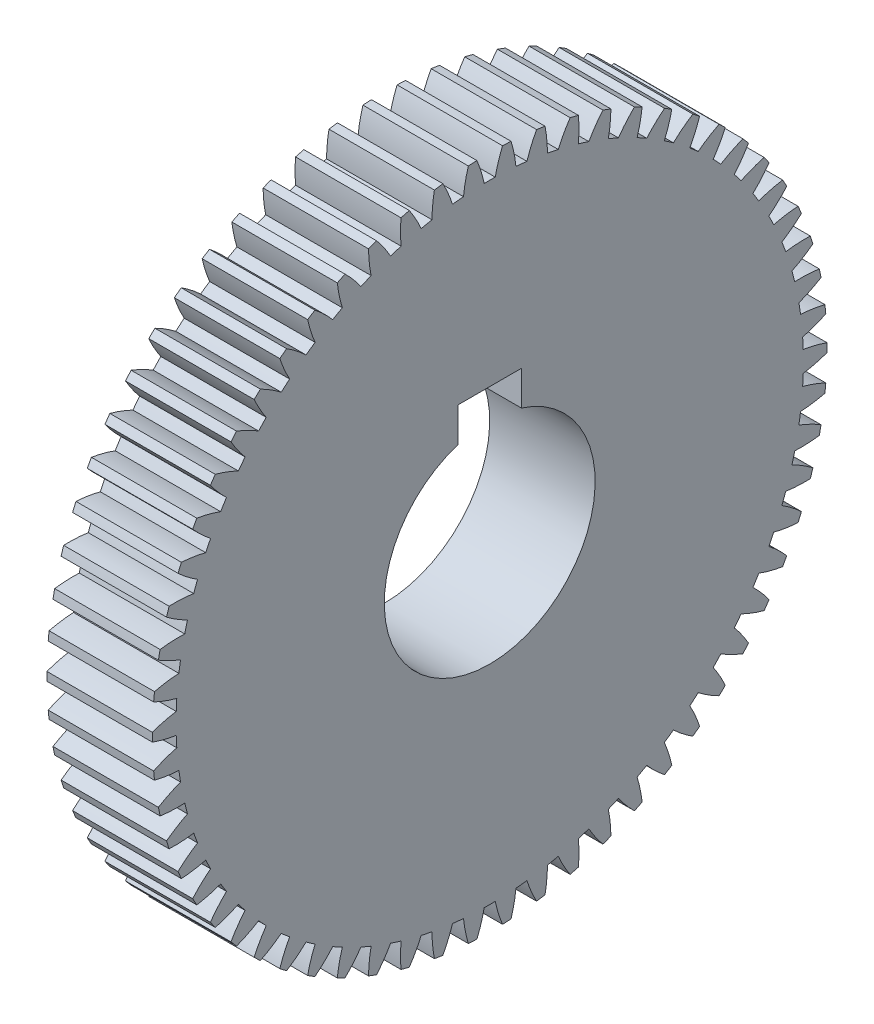
SolidWorks part; units mm, degrees
ref_plane "Plane1" through (0, 0, 0) normal (0, 0, 1) x (1, 0, 0)
ref_plane "Plane2" through (0, 0, 0) normal (0, 1, 0) x (1, 0, 0)
ref_plane "Plane3" through (0, 0, 0) normal (1, 0, 0) x (0, 0, -1)
sketch "HoldingSke" plane through (0, 0, 0) normal (0, 1, 0) x (1, 0, 0)
  line L0 (0, 0) -> (0.4695, -0.8829)
  line L1 (-15, 0) -> (100, 0) construction
  line L2 (0, 0) -> (-2.1039, 2.3779)
  line L3 (0, 0) -> (-11.863, 4.5341)
  line L4 (0, 0) -> (4.0544, 7.6251)
  line L5 (0, 0) -> (-46.8476, -17.4728)
  line L6 (0, 0) -> (-8.2896, -5.593)
  line L7 (-2.1039, 2.3779) -> (8.6586, 51.2059)
  line L8 (-76.2, 54.61) -> (-73.4, 54.61)
  line L9 (-67.7845, 28.3722) -> (-49.3413, 33.142)
  line L10 (-76.2, 71.12) -> (104.1128, 71.12)
  line L11 (0, 0) -> (-10, 0)
  line L12 (-76.2, 101.6) -> (-76.162, 101.6)
  line L13 (24.9733, 27.94) -> (52.9518, 28.4284)
  line L14 (24.9733, 27.94) -> (24.9743, 27.94)
  line L15 (24.9733, 27.94) -> (100.4006, 29.5858)
  line L16 (-63.627, -1) -> (-12.827, -1)
  circle A0 centre (0, 0) radius 10
  circle A1 centre (0, 0) radius 29.749
  circle A2 centre (0, 0) radius 37.5
  circle A3 centre (0, 0) radius 10
  dimension "MHD" = 59.498
  dimension "Hub_dia" = 75
  dimension "Bore" = 20
  dimension "MBD" = 20
  dimension "Num_teeth" = 62
  dimension "Pitch" = 1
  dimension "Overall_len" = 50
  dimension "Show_teeth" = 62
  dimension "Thickness" = 10
  dimension "OAL" = 50.0001
  dimension "T_dim" = 2.8
  dimension "Ap" = 14.5
  dimension "H" = 19.05
  dimension "Pitch_radius" = 180.3128
  dimension "Width" = 10
  dimension "Backlash" = 0.038
  dimension "Addendum_fac" = 1
  dimension "Dedendum_fac" = 1.25
  dimension "Clearance_fac" = 0.25
  dimension "Dedendum_add" = 0.001
  dimension "Module" = 1
sketch "BasProSke" plane through (0, 0, 0) normal (0, 1, 0) x (1, 0, 0)
  line L0 (-10, 0) -> (60, 0) construction
  line L1 (0, 0) -> (0, 32)
  line L2 (0, 0) -> (10, 0)
  line L3 (10, 0) -> (10, 32)
  line L4 (10, 32) -> (0, 32)
  dimension "Thickness" = 10
  dimension "Diameter" = 64
revolve "Base-Revolve" add sketch "BasProSke" angle 360 about L0
sketch "TooCutSke" plane through (0, 0, 0) normal (1, 0, 0) x (0, 0, -1)
  line L1 (0, 0) -> (0, 107) construction
  line L2 (0, 0) -> (-0.8518, 30.9883) construction
  line L3 (0, 0) -> (-3.1394, 61.9038) construction
  line L4 (-0.8518, 30.9883) -> (-1.5697, 30.9519) construction
  arc A0 (0.524, 29.7444) -> (-0.524, 29.7444) centre (0, 0) ccw
  arc A1 (1.2254, 32.0019) -> (-1.2254, 32.0019) centre (0, 0) ccw
  circle A2 centre (0, 0) radius 31 construction
  circle A3 centre (0, 0) radius 30.0126 construction
  arc A4 (-0.524, 29.7444) -> (-1.2254, 32.0019) centre (-12.6624, 27.2106) ccw
  arc A5 (1.2254, 32.0019) -> (0.524, 29.7444) centre (12.6624, 27.2106) ccw
  dimension "Root_dia" = 59.498
  dimension "Overcut_dia" = 64.0508
  dimension "Pitch_dia" = 62
  dimension "Base_dia" = 60.0252
  dimension "Flank_rad" = 12.4
  dimension "Half_ang" = 2.903
  dimension "Half_CT" = 0.7188
extrude "ToothCut" cut sketch "TooCutSke" along normal through all
fillet "Breaks" [suppressed] radius 0.02
fillet "RootFillets" [suppressed] radius 0.251
pattern_circular "TeethCuts" count 62 every 5.806 about axis through (-10, 0, 0) along (1, 0, 0) of "ToothCut", "RootFillets", "Breaks"
sketch "HubNeaOneSke" plane through (0, 0, 0) normal (-1, 0, 0) x (0, 0, 1)
  circle A0 centre (0, 0) radius 29.749
  dimension "Diameter" = 59.498
extrude "HubNearOne" [suppressed] add sketch "HubNeaOneSke" along normal blind 40.0001
sketch "HubNeaBotSke" plane through (0, 0, 0) normal (-1, 0, 0) x (0, 0, 1)
  circle A0 centre (0, 0) radius 29.749
  dimension "Diameter" = 59.498
extrude "HubNearBoth" [suppressed] add sketch "HubNeaBotSke" along normal blind 20
ref_plane "FarPln" through (10, 0, 0) normal (1, 0, 0) x (0, 0, -1)
sketch "HubFarSke" plane through (10, 0, 0) normal (1, 0, 0) x (0, 0, -1)
  circle A0 centre (0, 0) radius 29.749
  dimension "Diameter" = 59.498
extrude "HubFar" [suppressed] add sketch "HubFarSke" along normal blind 20
sketch "BorSke" plane through (0, 0, 0) normal (1, 0, 0) x (0, 0, -1)
  circle A0 centre (0, 0) radius 10
  dimension "Diameter" = 20
extrude "Bore" cut sketch "BorSke" along normal mid plane 100.0001
sketch "KeySke" plane through (0, 0, 0) normal (1, 0, 0) x (0, 0, -1)
  line L0 (-3, 0) -> (-3, 12.8)
  line L1 (-3, 12.8) -> (3, 12.8)
  line L2 (3, 12.8) -> (3, 0)
  line L3 (0, 0) -> (0, 34) construction
  line L4 (-3, 0) -> (3, 0)
  dimension "Offset" = 12.8
  dimension "Width" = 6
extrude "Keyway" cut sketch "KeySke" along normal mid plane 100.0001
pattern_circular "Keyway2" [suppressed] count 2 every 90 about axis through (-10, 0, 0) along (1, 0, 0)
equation "' \"Module@HoldingSke\" = 6.35"
equation "' \"Num_teeth@HoldingSke\" = 12"
equation "' \"Ap@HoldingSke\" =  20"
equation "' \"Ap@HoldingSke\" = 20"
equation "' \"Width@HoldingSke\" = 0.5 * 25.4"
equation "' \"Hub_dia@HoldingSke\"= 1 * 25.4"
equation "' \"Hub_dia@HoldingSke\" = 1 * 25.4"
equation "' \"Overall_len@HoldingSke\" = 1.0 * 25.4"
equation "' \"Bore@HoldingSke\" = 0.75 * 25.4"
equation "' \"T_dim@HoldingSke\" = 0.1 * 25.4"
equation "' \"Width@KeySke\" = 0.25 * 25.4"
equation "' \"Show_teeth@HoldingSke\" = 13"
equation "' \"Backlash@HoldingSke\" = 0.009 * 25.4"
equation "' \"Addendum_fac@HoldingSke\" = 1.0"
equation "' \"Dedendum_fac@HoldingSke\" = 1.25"
equation "' \"Dedendum_add@HoldingSke\" = 0.00005 * 25.4"
equation "' \"Clearance_fac@HoldingSke\" = 0.25"
equation "\"Pitch@HoldingSke\" = 1 / \"Module@HoldingSke\""
equation "\"Overcut_dia@TooCutSke\" = (\"Num_teeth@HoldingSke\" + 2 * \"Addendum_fac@HoldingSke\") / \"Pitch@HoldingSke\" + 0.002 * 25.4"
equation "\"Pitch_dia@TooCutSke\" = \"Num_teeth@HoldingSke\" / \"Pitch@HoldingSke\""
equation "\"Base_dia@TooCutSke\" = \"Num_teeth@HoldingSke\" / \"Pitch@HoldingSke\" * cos((\"Ap@HoldingSke\"  * 3.14159265 / 180))"
equation "\"Root_dia@TooCutSke\" = (\"Num_teeth@HoldingSke\" + 2) / \"Pitch@HoldingSke\" - 2 * (\"Addendum_fac@HoldingSke\" + \"Dedendum_fac@HoldingSke\") / \"Pitch@HoldingSke\" - \"Dedendum_add@HoldingSke\" * 2"
equation "\"Half_ang@TooCutSke\" = 180 / \"Num_teeth@HoldingSke\""
equation "\"Half_CT@TooCutSke\" = \"Num_teeth@HoldingSke\" / \"Pitch@HoldingSke\" * sin((3.14159265 / 2 / \"Num_teeth@HoldingSke\")) / 2 - 7 * \"Backlash@HoldingSke\" / 4"
equation "\"Flank_rad@TooCutSke\" = \"Num_teeth@HoldingSke\" / \"Pitch@HoldingSke\" / 5"
equation "\"Radius@RootFillets\" = \"Clearance_fac@HoldingSke\" / \"Pitch@HoldingSke\" + \"Dedendum_add@HoldingSke\""
equation "\"Break_rad@Breaks\" = 0.02 / \"Pitch@HoldingSke\""
equation "\"Thickness@HoldingSke\" = \"Width@HoldingSke\""
equation "\"OAL@HoldingSke\" = \"Thickness@HoldingSke\""
equation "\"MHD@HoldingSke\" = (\"Num_teeth@HoldingSke\" + 2) / \"Pitch@HoldingSke\" - 2 * (\"Addendum_fac@HoldingSke\" + \"Dedendum_fac@HoldingSke\")  / \"Pitch@HoldingSke\" - \"Dedendum_add@HoldingSke\" * 2"
equation "\"MBD@HoldingSke\" = (\"Num_teeth@HoldingSke\" + 2) / \"Pitch@HoldingSke\" - 2 * (\"Addendum_fac@HoldingSke\" + \"Dedendum_fac@HoldingSke\")  / \"Pitch@HoldingSke\" - \"Dedendum_add@HoldingSke\" * 2 - 0.002 * 25.4"
equation "\"MHD@HoldingSke\" = ((sgn( \"MHD@HoldingSke\" - \"Hub_dia@HoldingSke\" )-1)*( \"MHD@HoldingSke\" - \"Hub_dia@HoldingSke\" ))/-2+ \"Hub_dia@HoldingSke\""
equation "\"MBD@HoldingSke\" = ((sgn( \"MBD@HoldingSke\" - \"Bore@HoldingSke\" )-1)*( \"MBD@HoldingSke\" - \"Bore@HoldingSke\" ))/-2+ \"Bore@HoldingSke\""
equation "\"OAL@HoldingSke\" = ((sgn( \"OAL@HoldingSke\" - \"Overall_len@HoldingSke\" )+1)*( \"OAL@HoldingSke\" - \"Overall_len@HoldingSke\" ))/2 + \"Overall_len@HoldingSke\" + 0.000002 * 25.4"
equation "\"Num_teeth@TeethCuts\" = int( \"Show_teeth@HoldingSke\" ) + 1"
equation "\"Num_teeth@TeethCuts\" = ((sgn( \"Num_teeth@TeethCuts\" - \"Num_teeth@HoldingSke\" )-1)*( \"Num_teeth@TeethCuts\" - \"Num_teeth@HoldingSke\" ))/-2+ \"Num_teeth@HoldingSke\""
equation "\"Num_teeth@TeethCuts\" = ((sgn( \"Num_teeth@TeethCuts\" - 2.0)+1)*( \"Num_teeth@TeethCuts\" - 2.0))/2 +2.0"
equation "\"Angle@TeethCuts\" = 360.0 / \"Num_teeth@HoldingSke\""
equation "\"Diameter@BasProSke\" = (\"Num_teeth@HoldingSke\" + 2 * \"Addendum_fac@HoldingSke\") / \"Pitch@HoldingSke\""
equation "\"Thickness@BasProSke\"  = \"Thickness@HoldingSke\""
equation "' \"Fillet_rad@BasProSke\" =  \"Thickness@HoldingSke\" * 0.05"
equation "' \"Fillet_rad@BasProSke\" = \"Thickness@HoldingSke\" * 0.05"
equation "\"MHD@HoldingSke\" = ((sgn( \"MHD@HoldingSke\" - \"Root_dia@TooCutSke\" )-1)*( \"MHD@HoldingSke\" - \"Root_dia@TooCutSke\" ))/-2+ \"Root_dia@TooCutSke\""
equation "\"Diameter@HubNeaOneSke\" = \"MHD@HoldingSke\""
equation "\"Length@HubNearOne\" = \"OAL@HoldingSke\" - \"Thickness@BasProSke\""
equation "\"Diameter@HubNeaBotSke\" = \"MHD@HoldingSke\""
equation "\"Length@HubNearBoth\" = ( \"OAL@HoldingSke\" - \"Thickness@BasProSke\" ) / 2.0"
equation "\"Thickness@FarPln\" = \"Thickness@BasProSke\""
equation "\"Diameter@HubFarSke\" = \"MHD@HoldingSke\""
equation "\"Length@HubFar\" = ( \"OAL@HoldingSke\" - \"Thickness@BasProSke\" ) / 2.0"
equation "\"Diameter@BorSke\" = \"MBD@HoldingSke\""
equation "\"D1@Bore\" = \"OAL@HoldingSke\" * 2.0"
equation "\"D1@Keyway\" = \"OAL@HoldingSke\" * 2.0"
equation "\"Offset@KeySke\" = \"T_dim@HoldingSke\" + \"MBD@HoldingSke\" / 2.0"
